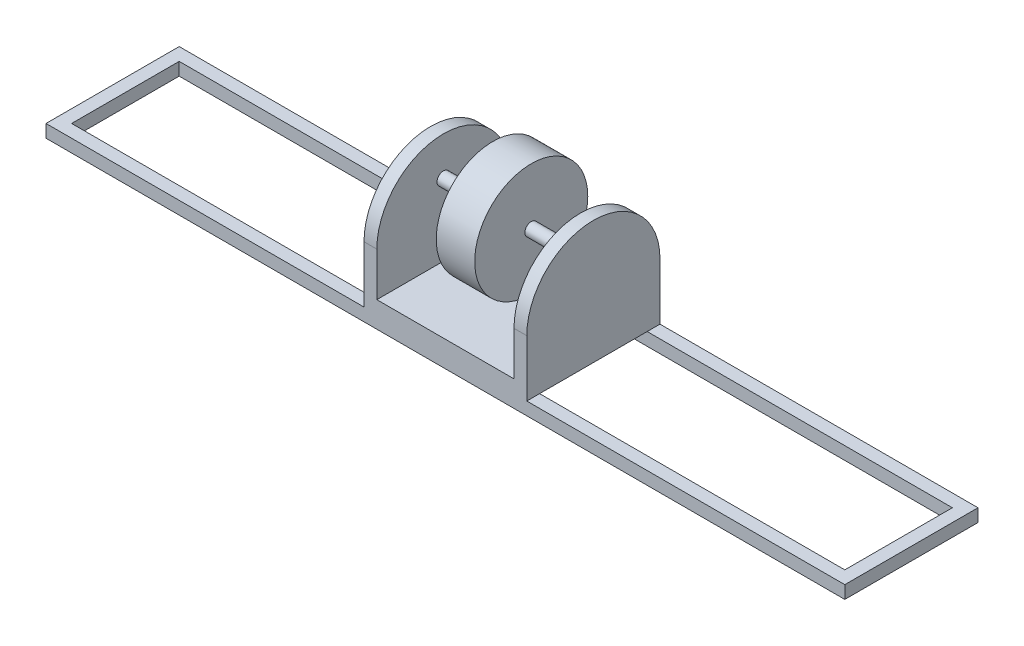
SolidWorks part; units mm, degrees
ref_plane "Front Plane" through (0, 0, 0) normal (0, 0, 1) x (1, 0, 0)
ref_plane "Top Plane" through (0, 0, 0) normal (0, 1, 0) x (1, 0, 0)
ref_plane "Right Plane" through (0, 0, 0) normal (1, 0, 0) x (0, 0, -1)
sketch "Sketch1" plane through (0, 0, 0) normal (0, 1, 0) x (1, 0, 0)
  line L0 (-623.25, -623.25) -> (-623.25, 623.25)
  line L5 (-603.25, -603.25) -> (603.25, -603.25)
  line L6 (-603.25, -603.25) -> (-603.25, 603.25)
  line L7 (-603.25, 603.25) -> (603.25, 603.25)
  line L8 (603.25, -603.25) -> (603.25, 603.25)
  line L9 (-603.25, -603.25) -> (603.25, 603.25) construction
  line L10 (-603.25, 603.25) -> (603.25, -603.25) construction
  line L11 (-623.25, 623.25) -> (623.25, 623.25)
  line L12 (623.25, -623.25) -> (623.25, 623.25)
  line L13 (-623.25, -623.25) -> (623.25, -623.25)
  line L14 (-623.25, 623.25) -> (-623.25, 811.0948)
  line L15 (-623.25, 811.0948) -> (623.25, 811.0948)
  line L16 (623.25, 811.0948) -> (623.25, 623.25)
  line L17 (-603.25, 623.25) -> (-603.25, 791.0948)
  line L18 (-603.25, 791.0948) -> (603.25, 791.0948)
  line L19 (603.25, 791.0948) -> (603.25, 623.25)
  line L20 (603.25, 603.25) -> (623.25, 603.25)
  line L21 (-603.25, 603.25) -> (-623.25, 603.25)
  circle A2 centre (0, 0) radius 603.25 construction
  dimension "D1" = 20
  dimension "D2" = 20
extrude "Boss-Extrude1" add sketch "Sketch1" along normal blind 20 contours L18 L19 L11 L16 L15 L14 L17 | L21 L7 L20 L12 L11 L0
sketch "Sketch2" plane through (0, 20, 0) normal (0, 1, 0) x (1, 0, 0)
  line L0 (-623.25, 811.0948) -> (623.25, 811.0948) construction
  line L1 (127, 811.0948) -> (-127, 811.0948)
  line L2 (127, 811.0948) -> (127, 603.25)
  line L3 (127, 603.25) -> (-127, 603.25)
  line L4 (-127, 811.0948) -> (-127, 603.25)
  line L5 (127, 811.0948) -> (-127, 603.25) construction
  line L6 (127, 603.25) -> (-127, 811.0948) construction
  line L7 (-603.25, 603.25) -> (603.25, 603.25) construction
  point P4 (0, 707.1724)
  point P9 (0, 0)
  point P12 (0, 0)
extrude "Boss-Extrude2" add sketch "Sketch2" along normal blind 20
sketch "Sketch3" plane through (-127, 0, 0) normal (-1, 0, 0) x (0, 0, 1)
  line L4 (-811.0948, 40) -> (-603.25, 40)
  line L5 (-811.0948, 40) -> (-811.0948, 108.2791)
  line L7 (-603.25, 40) -> (-603.25, 108.2791)
  line L8 (-811.0948, 40) -> (-603.25, 108.2791) construction
  line L9 (-811.0948, 108.2791) -> (-603.25, 40) construction
  arc A2 (-811.0948, 108.2791) -> (-603.25, 108.2791) centre (-707.1724, 108.2791) cw
  circle A3 centre (-707.1724, 152.0694) radius 10
  point P4 (-707.1724, 74.1396)
extrude "Boss-Extrude3" add sketch "Sketch3" against normal blind 20
mirror "Mirror1" about plane through (0, 0, 0) normal (1, 0, 0) of "Boss-Extrude3"
sketch "Sketch4" plane through (0, 0, 0) normal (1, 0, 0) x (0, 0, -1)
  circle A0 centre (707.1724, 152.0694) radius 88.2446
extrude "Boss-Extrude4" add sketch "Sketch4" along normal blind 30 and the other way blind 30 separate body
sketch "Sketch5" plane through (-127, 0, 0) normal (-1, 0, 0) x (0, 0, 1)
  circle A0 centre (-707.1724, 152.0694) radius 10 construction
  circle A1 centre (-707.1724, 152.0694) radius 10
extrude "Boss-Extrude5" add sketch "Sketch5" against normal up to surface (254 mm away) up to face at (127, 66.7468, -707.1724)
